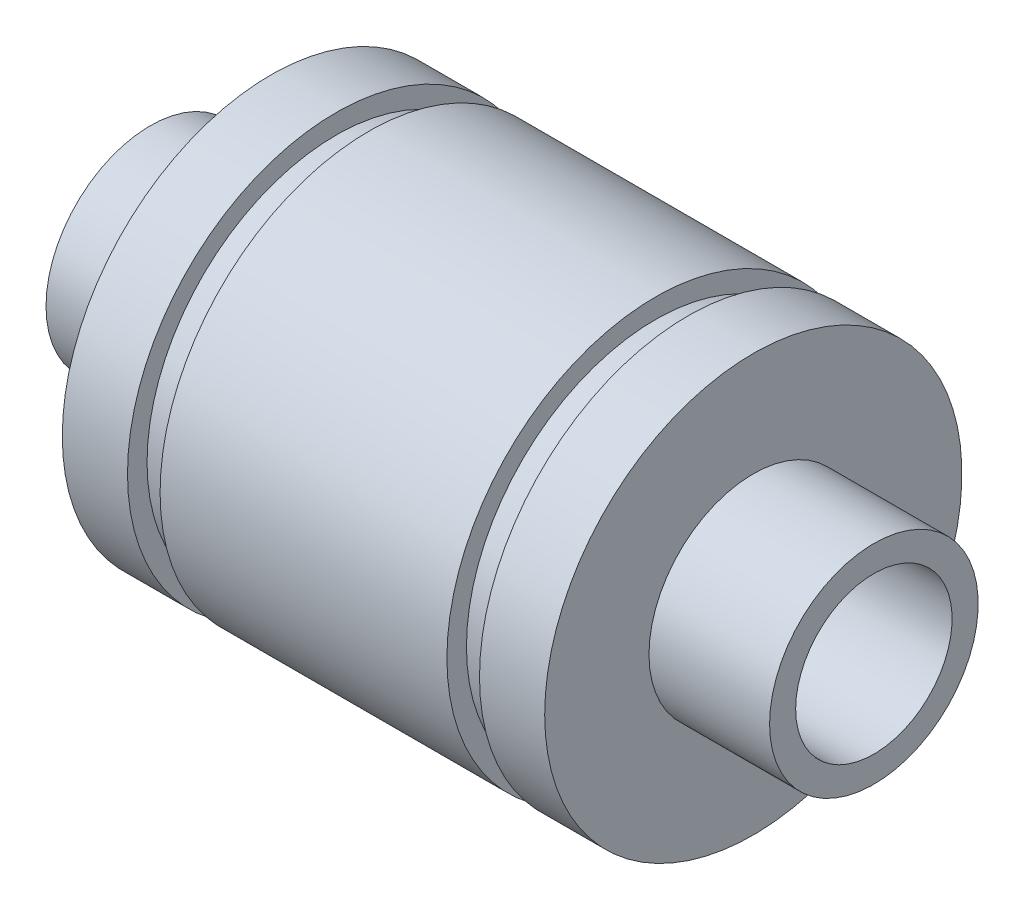
SolidWorks part; units mm, degrees
ref_plane "Alzado" through (0, 0, 0) normal (0, 0, 1) x (1, 0, 0)
ref_plane "Planta" through (0, 0, 0) normal (0, 1, 0) x (1, 0, 0)
ref_plane "Vista lateral" through (0, 0, 0) normal (1, 0, 0) x (0, 0, -1)
sketch "Croquis1" plane through (0, 0, 0) normal (0, 1, 0) x (1, 0, 0)
  circle A0 centre (0, 0) radius 16
  dimension "D1" = 32
sketch "Croquis2" plane through (0, 0, 0) normal (0, 0, 1) x (1, 0, 0)
  line L0 (0, 0) -> (18.5, 0)
  line L1 (16, 0) -> (-16, 0) construction
  line L3 (18.5, 16) -> (-18.5, 16) construction
  line L4 (-18.5, 16) -> (-18.5, 8)
  line L7 (-12.75, 0) -> (0, 0)
  line L8 (-18.5, 8) -> (-27.75, 8)
  line L9 (-27.75, 8) -> (-27.75, 0)
  line L10 (-27.75, 0) -> (-12.75, 0)
  line L11 (18.5, 16) -> (18.5, 8)
  line L12 (18.5, 8) -> (27.75, 8)
  line L13 (27.75, 8) -> (27.75, 0)
  line L14 (27.75, 0) -> (18.5, 0)
  line L15 (-18.5, 16) -> (-13.5, 16)
  line L16 (-13.5, 16) -> (-13.5, 14.5)
  line L17 (-13.5, 14.5) -> (-11, 14.5)
  line L18 (-11, 14.5) -> (-11, 16)
  line L19 (-11, 16) -> (11, 16)
  line L20 (11, 16) -> (11, 14.5)
  line L21 (11, 14.5) -> (13.5, 14.5)
  line L22 (13.5, 14.5) -> (13.5, 16)
  line L23 (13.5, 16) -> (18.5, 16)
  dimension "D1" = 16
  dimension "D2" = 37
  dimension "D3" = 18.5
  dimension "D4" = 8
  dimension "D5" = 8
  dimension "D6" = 9.25
  dimension "D7" = 9.25
  dimension "D8" = 8
  dimension "D9" = 15
  dimension "D10" = 2.5
  dimension "D11" = 2.5
  dimension "D12" = 5
  dimension "D13" = 5
  dimension "D14" = 1.5
  dimension "D15" = 1.5
revolve "Revolución1" add sketch "Croquis2" angle 360 about L7
sketch "Croquis3" plane through (-27.75, 0, 0) normal (-1, 0, 0) x (0, 0, 1)
  circle A0 centre (0, 0) radius 6
  dimension "D1" = 12
extrude "Cortar-Extruir1" cut sketch "Croquis3" against normal through all
